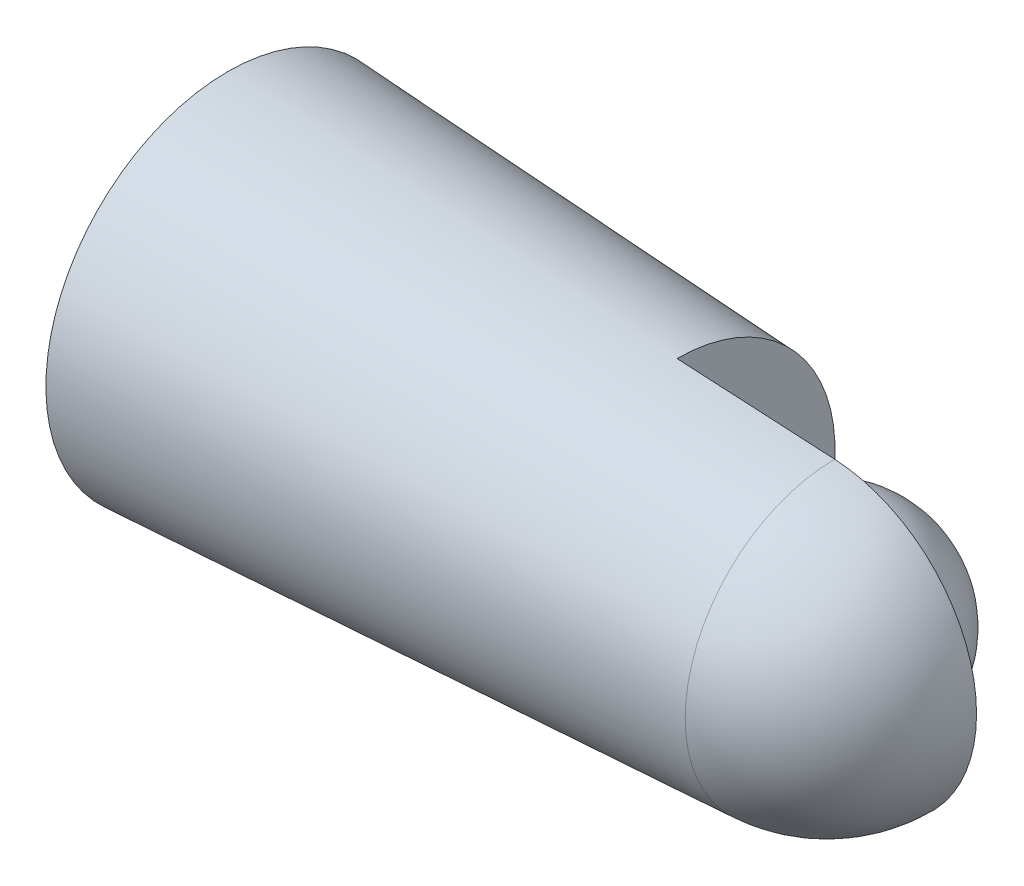
SolidWorks part; units mm, degrees
ref_plane "Front Plane" through (0, 0, 0) normal (0, 0, 1) x (1, 0, 0)
ref_plane "Top Plane" through (0, 0, 0) normal (0, 1, 0) x (1, 0, 0)
ref_plane "Right Plane" through (0, 0, 0) normal (1, 0, 0) x (0, 0, -1)
sketch "Sketch1" plane through (0, 0, 0) normal (0, 1, 0) x (1, 0, 0)
  line L0 (35, 0) -> (-140, 0)
  line L1 (-140, 0) -> (-140, 42.5)
  line L2 (-140, 42.5) -> (1.86, 34.9505)
  arc A0 (35, 0) -> (1.86, 34.9505) centre (0, 0) ccw
  dimension "D1" = 70
  dimension "D2" = 175
  dimension "D3" = 42.5
revolve "Revolve1" add sketch "Sketch1" angle 360 about L0
sketch "Sketch2" plane through (-140, 0, 0) normal (-1, 0, 0) x (0, 0, 1)
  circle A0 centre (0, 0) radius 35
  dimension "D1" = 70
extrude "Cut-Extrude1" cut sketch "Sketch2" against normal blind 20
sketch "Sketch3" plane through (0, 0, 0) normal (0, 0, 1) x (1, 0, 0)
  line L1 (35, -50) -> (-35, -50)
  line L2 (35, -50) -> (35, 50)
  line L3 (35, 50) -> (-35, 50)
  line L4 (-35, -50) -> (-35, 50)
  line L5 (35, -50) -> (-35, 50) construction
  line L6 (35, 50) -> (-35, -50) construction
  point P0 (0, 0)
  dimension "D1" = 70
  dimension "D2" = 100
extrude "Cut-Extrude2" cut sketch "Sketch3" against normal blind 53
sketch "Sketch4" plane through (0, 0, 0) normal (0, 0, 1) x (1, 0, 0)
  line L0 (25, 0) -> (-25, 0)
  arc A0 (25, 0) -> (-25, 0) centre (0, 0) ccw
  dimension "D1" = 50
revolve "Revolve2" add sketch "Sketch4" angle 360 about L0
